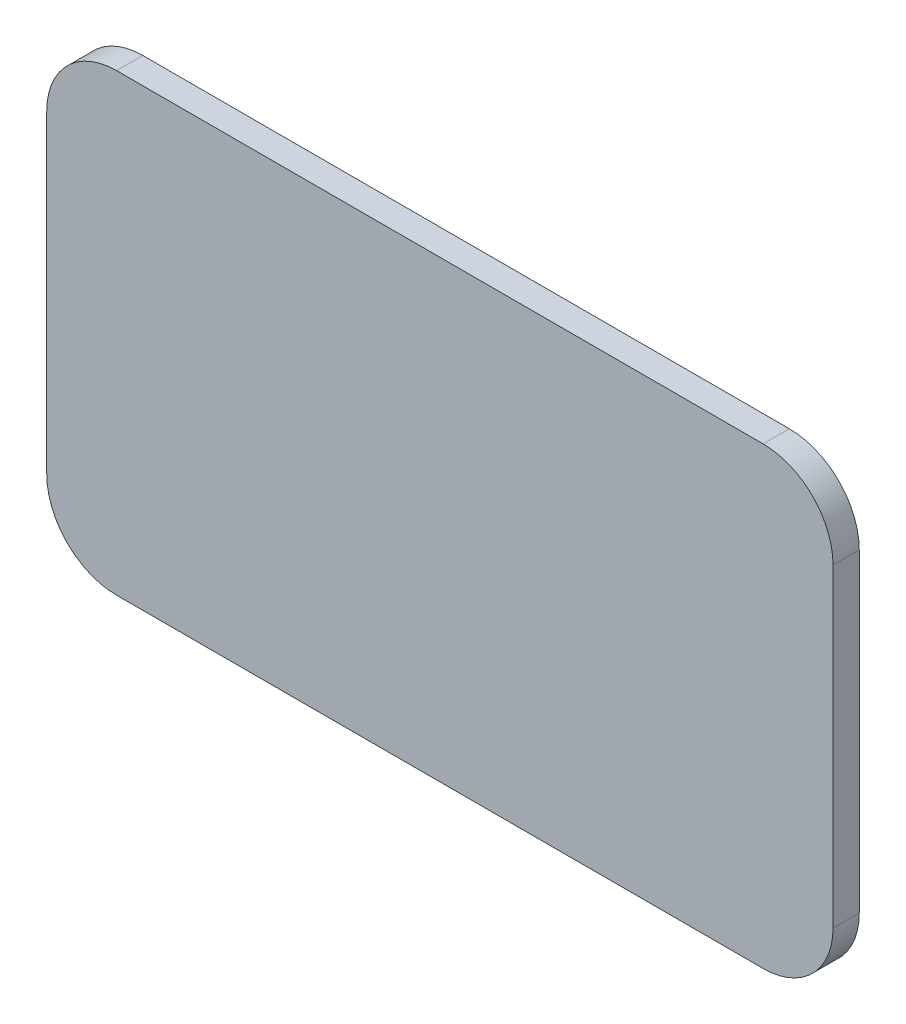
SolidWorks part; units mm, degrees
ref_plane "Front Plane" through (0, 0, 0) normal (0, 0, 1) x (1, 0, 0)
ref_plane "Top Plane" through (0, 0, 0) normal (0, 1, 0) x (1, 0, 0)
ref_plane "Right Plane" through (0, 0, 0) normal (1, 0, 0) x (0, 0, -1)
sketch "Sketch1" plane through (0, 0, 0) normal (0, 0, 1) x (1, 0, 0)
  line L1 (0, 0) -> (45, 0)
  line L2 (0, 0) -> (0, -26)
  line L3 (0, -26) -> (45, -26)
  line L4 (45, 0) -> (45, -26)
  dimension "D1" = 45
  dimension "D2" = 26
extrude "Boss-Extrude1" add sketch "Sketch1" along normal blind 1.5
sketch "Sketch2" plane through (0, 0, 1.5) normal (0, 0, 1) x (1, 0, 0)
  line L0 (0, 0) -> (0, -26) construction
  line L1 (17, -5) -> (33, -5) construction
  line L2 (17, -5) -> (17, -21) construction
  line L3 (17, -21) -> (33, -21) construction
  line L4 (33, -5) -> (33, -21) construction
  line L5 (45, -26) -> (45, 0) construction
  line L7 (20.5, -9.5) -> (29.5, -9.5)
  line L8 (20.5, -9.5) -> (20.5, -16.5)
  line L9 (20.5, -16.5) -> (29.5, -16.5)
  line L10 (29.5, -9.5) -> (29.5, -16.5)
  point P4 (17, -13)
  point P7 (0, -13)
  point P14 (29.5, -13)
  point P15 (33, -13)
  point P16 (25, -16.5)
  point P17 (25, -21)
  dimension "D1" = 16
  dimension "D2" = 12
  dimension "D3" = 7
  dimension "D4" = 9
extrude "Boss-Extrude2" [suppressed] add sketch "Sketch2" along normal blind 8
fillet "Fillet1" radius 4 4 edges at (0, -26, 0.75) (0, 0, 0.75) (45, 0, 0.75) (45, -26, 0.75)
